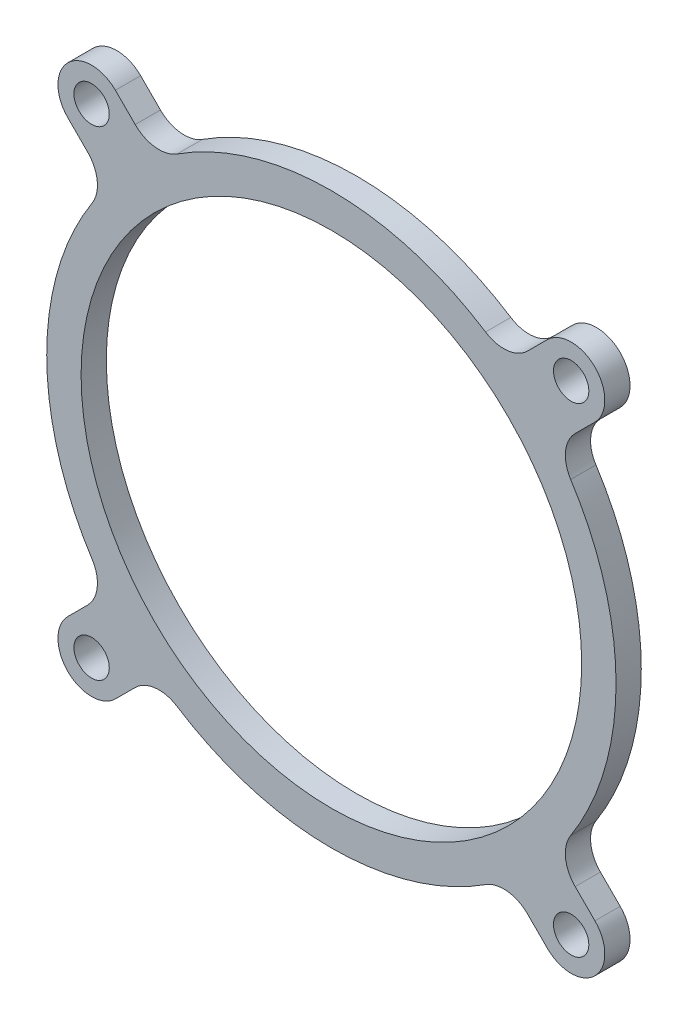
SolidWorks part; units mm, degrees
ref_plane "前视基准面" through (0, 0, 0) normal (0, 0, 1) x (1, 0, 0)
ref_plane "上视基准面" through (0, 0, 0) normal (0, 1, 0) x (1, 0, 0)
ref_plane "右视基准面" through (0, 0, 0) normal (1, 0, 0) x (0, 0, -1)
sketch "草图1" plane through (0, 0, 0) normal (0, 0, 1) x (1, 0, 0)
  line L0 (0, 0) -> (47.1, 0) construction
  line L2 (0, 0) -> (47.1, -47.1) construction
  line L3 (47.1, -47.1) -> (52.0497, -52.0497) construction
  line L6 (54.05, 6.95) -> (-6.95, 6.95) construction
  line L8 (23.55, -23.55) -> (23.55, -16.6688) construction
  line L14 (52.0497, -52.0497) -> (48.0497, -56.0497) construction
  line L23 (-1.2931, 6.95) -> (48.3931, 6.95) construction
  line L27 (49.2213, -54.8782) -> (46.8701, -52.5269)
  line L28 (54.8782, -49.2213) -> (52.5269, -46.8701)
  line L29 (-2.1213, -54.8782) -> (0.2299, -52.5269)
  line L47 (-7.7782, -49.2213) -> (-5.4269, -46.8701)
  line L48 (-7.7782, 2.1213) -> (-5.4269, -0.2299)
  line L49 (23.55, -23.55) -> (41.8752, 4.8928) construction
  line L53 (-2.1213, 7.7782) -> (0.2299, 5.4269)
  line L60 (49.2213, 7.7782) -> (46.8701, 5.4269)
  line L61 (54.8782, 2.1213) -> (52.5269, -0.2299)
  circle A15 centre (52.0497, -52.0497) radius 2.1
  circle A16 centre (52.0497, -52.0497) radius 4 construction
  arc A17 (49.2213, -54.8782) -> (54.8782, -49.2213) centre (52.0497, -52.0497) ccw
  arc A18 (-7.7782, -49.2213) -> (-2.1213, -54.8782) centre (-4.9497, -52.0497) ccw
  arc A19 (-2.1213, 7.7782) -> (-7.7782, 2.1213) centre (-4.9497, 4.9497) ccw
  arc A20 (54.8782, 2.1213) -> (49.2213, 7.7782) centre (52.0497, 4.9497) ccw
  circle A25 centre (-4.9497, -52.0497) radius 2.1
  circle A26 centre (-4.9497, 4.9497) radius 2.1
  circle A27 centre (52.0497, 4.9497) radius 2.1
  circle A31 centre (23.55, -23.55) radius 33.835 construction
  arc A32 (5.2248, -51.9928) -> (41.8752, -51.9928) centre (23.55, -23.55) ccw
  arc A33 (51.9928, -41.8752) -> (51.9928, -5.2248) centre (23.55, -23.55) ccw
  arc A34 (5.2248, 4.8928) -> (41.8752, 4.8928) centre (23.55, -23.55) cw
  arc A35 (-4.8928, -5.2248) -> (-4.8928, -41.8752) centre (23.55, -23.55) ccw
  arc A36 (-4.8928, -5.2248) -> (-5.4269, -0.2299) centre (-8.2553, -3.0584) ccw
  arc A37 (0.2299, 5.4269) -> (5.2248, 4.8928) centre (3.0584, 8.2553) ccw
  arc A38 (41.8752, 4.8928) -> (46.8701, 5.4269) centre (44.0416, 8.2553) ccw
  arc A39 (52.5269, -0.2299) -> (51.9928, -5.2248) centre (55.3553, -3.0584) ccw
  arc A40 (51.9928, -41.8752) -> (52.5269, -46.8701) centre (55.3553, -44.0416) ccw
  arc A41 (46.8701, -52.5269) -> (41.8752, -51.9928) centre (44.0416, -55.3553) ccw
  arc A42 (5.2248, -51.9928) -> (0.2299, -52.5269) centre (3.0584, -55.3553) ccw
  arc A43 (-5.4269, -46.8701) -> (-4.8928, -41.8752) centre (-8.2553, -44.0416) ccw
  circle A49 centre (23.55, -23.55) radius 29.75
  point P67 (50.1356, -44.4788)
  point P70 (44.4788, -50.1356)
  dimension "D2" = 4
  dimension "D3" = 59.5
  dimension "D8" = 4
  dimension "D5" = 4
  dimension "D1" = 47.1
  dimension "D11" = 4
extrude "凸台-拉伸1" add sketch "草图1" along normal blind 3
